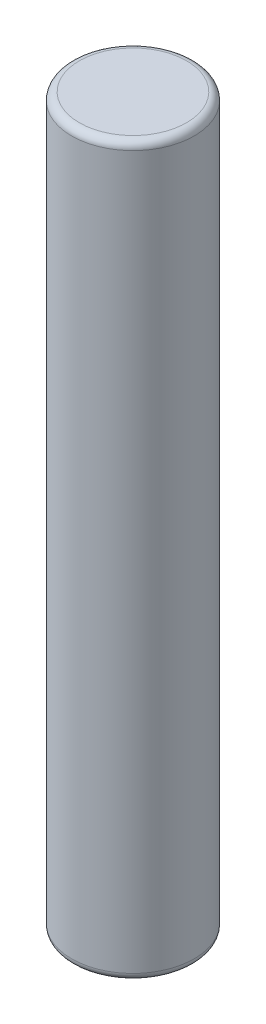
SolidWorks part; units mm, degrees
ref_plane "Front Plane" through (0, 0, 0) normal (0, 0, 1) x (1, 0, 0)
ref_plane "Top Plane" through (0, 0, 0) normal (0, 1, 0) x (1, 0, 0)
ref_plane "Right Plane" through (0, 0, 0) normal (1, 0, 0) x (0, 0, -1)
sketch "Sketch1" plane through (0, 0, 0) normal (0, 1, 0) x (1, 0, 0)
  circle A0 centre (0, 0) radius 0.8
  dimension "D1" = 1.6
extrude "Boss-Extrude1" add sketch "Sketch1" along normal blind 9.5
fillet "Fillet1" radius 0.1 2 edges at (0, 9.5, 0.8) (0, 0, 0.8)
